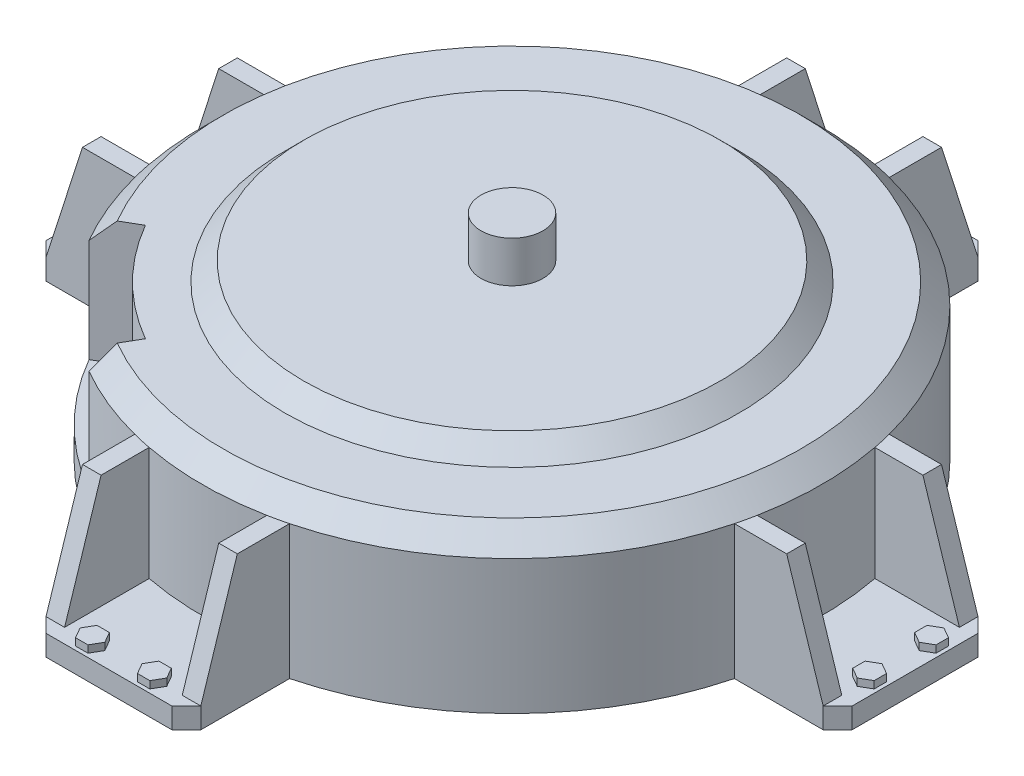
SolidWorks part; units mm, degrees
ref_plane "Front Plane" through (0, 0, 0) normal (0, 0, 1) x (1, 0, 0)
ref_plane "Top Plane" through (0, 0, 0) normal (0, 1, 0) x (1, 0, 0)
ref_plane "Right Plane" through (0, 0, 0) normal (1, 0, 0) x (0, 0, -1)
sketch "Sketch1" plane through (0, 0, 0) normal (0, 1, 0) x (1, 0, 0)
  circle A0 centre (0, 0) radius 150
  dimension "D1" = 300
extrude "Boss-Extrude1" add sketch "Sketch1" along normal blind 75
chamfer "Chamfer1" distance 10 angle 45 1 edges at (0, 75, 150)
sketch "Sketch2" plane through (0, 75, 0) normal (0, 1, 0) x (1, 0, 0)
  line L0 (0, 0) -> (-237.3748, 0) construction
  line L1 (-145.2369, 37.5) -> (-195.2369, 37.5)
  line L2 (-195.2369, 37.5) -> (-195.2369, -37.5)
  line L3 (-195.2369, -37.5) -> (-145.2369, -37.5)
  circle A0 centre (0, 0) radius 150 construction
  circle A1 centre (0, 0) radius 150
  dimension "D1" = 75
  dimension "D2" = 50
extrude "Boss-Extrude2" add sketch "Sketch2" along normal blind 10 from offset 75 contours L0 A1 L1 L2 | A1 L0 L2 L3 offset against normal yes
chamfer "Chamfer2" distance 7 angle 45 2 edges at (-195.2369, 5, 37.5) (-195.2369, 5, -37.5)
sketch "Sketch3" plane through (0, 0, 37.5) normal (0, 0, 1) x (1, 0, 0)
  line L0 (-188.2369, 10) -> (-145.2369, 10)
  line L1 (-145.2369, 10) -> (-145.2369, 65)
  line L2 (-150, 65) -> (150, 65) construction
  line L3 (-145.2369, 65) -> (-170.5569, 65)
  line L4 (-170.5569, 65) -> (-188.2369, 10)
  dimension "D1" = 17.68
  dimension "D2" = 25.32
extrude "Boss-Extrude3" add sketch "Sketch3" against normal blind 9
sketch "Sketch5" plane through (0, 10, 0) normal (0, 1, 0) x (1, 0, 0)
  line L0 (-149.929, 4.6131) -> (-253.6188, 4.6131) construction
  line L1 (-188.2369, 37.5) -> (-188.2369, -37.5) construction
  line L3 (-183.0407, -18) -> (-183.0407, -12)
  line L4 (-183.0407, -12) -> (-188.2369, -9)
  line L5 (-188.2369, -9) -> (-193.433, -12)
  line L6 (-193.433, -12) -> (-193.433, -18)
  line L7 (-193.433, -18) -> (-188.2369, -21)
  line L8 (-188.2369, -21) -> (-183.0407, -18)
  arc A0 (-145.2369, 37.5) -> (-147.2676, -28.5) centre (0, 0) ccw construction
  circle A1 centre (-188.2369, -15) radius 5.1962 construction
  dimension "D1" = 6
  dimension "D2" = 13.5
extrude "Boss-Extrude4" add sketch "Sketch5" along normal blind 3.5
mirror "Mirror1" about plane through (0, 0, 0) normal (0, 0, 1) of "Boss-Extrude4", "Boss-Extrude3"
pattern_circular "CirPattern1" count 4 over 360 about axis through (0, 0, 0) along (0, 1, 0) of "Boss-Extrude2", "Chamfer2", "Boss-Extrude3", "Boss-Extrude4", "Mirror1"
sketch "Sketch6" plane through (0, 75, 0) normal (0, 1, 0) x (1, 0, 0)
  line L0 (0, 290.2736) -> (0, -315.8518) construction
  line L1 (301.5125, 0) -> (-334.8417, 0) construction
  line L2 (-112.5833, -65) -> (-129.9038, -75)
  line L3 (-65, -112.5833) -> (-75, -129.9038)
  arc A0 (0, -130) -> (-130, 0) centre (0, 0) ccw
  circle A1 centre (0, 0) radius 140 construction
  arc A2 (0, -140) -> (-140, 0) centre (0, 0) ccw
  arc A3 (-112.5833, -65) -> (-65, -112.5833) centre (0, 0) ccw
  arc A5 (-145.2369, -37.5) -> (-37.5, -145.2369) centre (0, 0) ccw construction
  arc A6 (-129.9038, -75) -> (-75, -129.9038) centre (0, 0) ccw
  circle M7 centre (0, 0) radius 140
  dimension "D1" = 260
  dimension "D2" = 30
  dimension "D3" = 30
extrude "Cut-Extrude1" cut sketch "Sketch6" against normal blind 60 contours L2 A6 L3 M7 | A3 L2 L3 M7
sketch "Sketch7" plane through (0, 75, 0) normal (0, 1, 0) x (1, 0, 0)
  circle A0 centre (0, 0) radius 110
  dimension "D1" = 220
extrude "Boss-Extrude5" add sketch "Sketch7" along normal blind 9 draft 45
sketch "Sketch8" plane through (0, 84, 0) normal (0, 1, 0) x (1, 0, 0)
  circle A0 centre (0, 0) radius 15
  dimension "D1" = 30
extrude "Boss-Extrude6" add sketch "Sketch8" along normal blind 20
